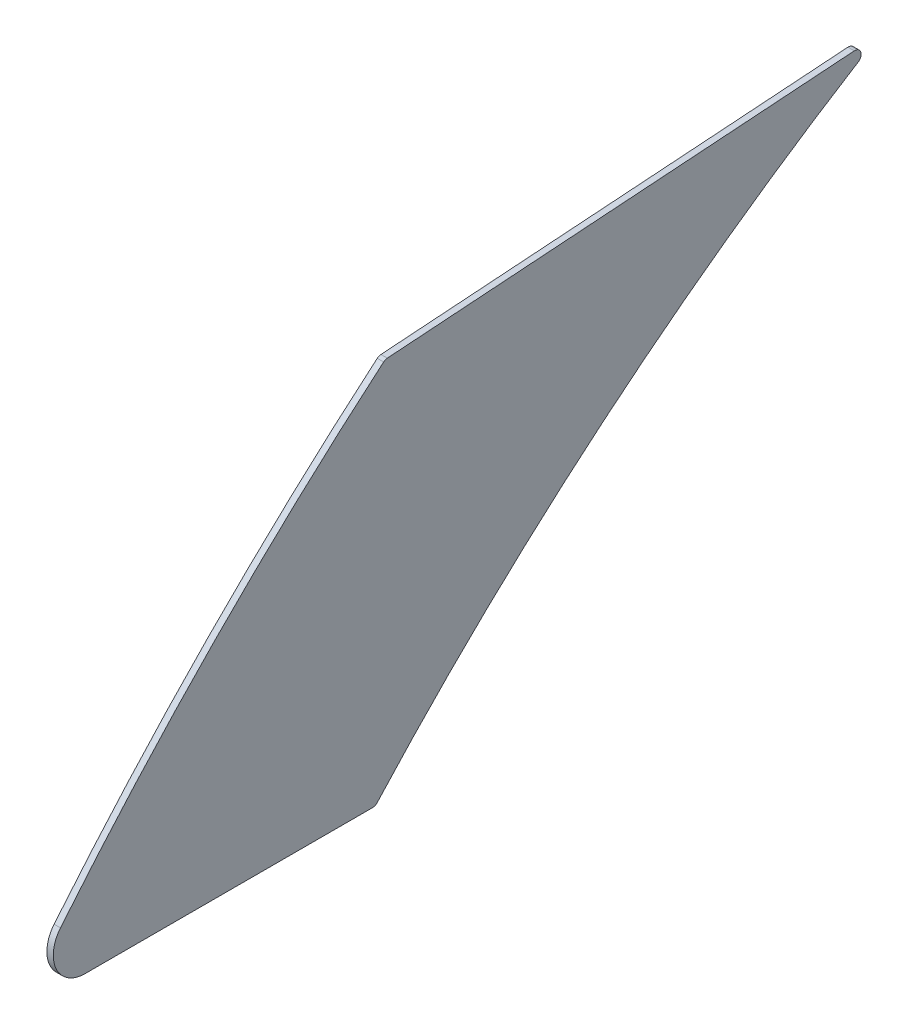
SolidWorks part; units mm, degrees
ref_plane "Front Plane" through (0, 0, 0) normal (0, 0, 1) x (1, 0, 0)
ref_plane "Top Plane" through (0, 0, 0) normal (0, 1, 0) x (1, 0, 0)
ref_plane "Right Plane" through (0, 0, 0) normal (1, 0, 0) x (0, 0, -1)
sketch "Sketch1" plane through (0, 0, 0) normal (1, 0, 0) x (0, 0, -1)
  line L0 (0.3265, 0.0228) -> (73.7167, 5.1548)
  line L1 (-47.1688, -60) -> (-2, -60)
  arc A0 (-1.2582, -59.6706) -> (74.3123, 3.3067) centre (258.3719, -294.388) cw
  arc A1 (-51.0357, -51.8304) -> (-0.2501, -0.2118) centre (258.3207, -305.4021) cw
  arc A2 (-47.1688, -60) -> (-51.0357, -51.8304) centre (-47.1688, -55) cw
  arc A3 (-2, -60) -> (-1.2582, -59.6706) centre (-2, -59) ccw
  arc A4 (0.3265, 0.0228) -> (-0.2501, -0.2118) centre (0.3963, -0.9747) ccw
  arc A5 (73.7167, 5.1548) -> (74.3123, 3.3067) centre (73.7864, 4.1572) cw
  point P9 (-57.5556, -60)
  point P10 (0, 0)
  point P11 (0, 0)
  point P12 (0, 0)
  point P15 (-1.5556, -60)
  point P18 (0, 0)
  point P21 (77.81, 5.441)
  point P22 (0, 0)
  point P23 (0, 0)
  point P24 (-1.7349, -62)
  dimension "D5" = 400
  dimension "D6" = 350
  dimension "D7" = 5
  dimension "D4" = 1
  dimension "D1" = 78
  dimension "D2" = 60
  dimension "D3" = 56
  dimension "D8" = 4
  dimension "D9" = 2
extrude "Boss-Extrude1" add sketch "Sketch1" along normal blind 1
